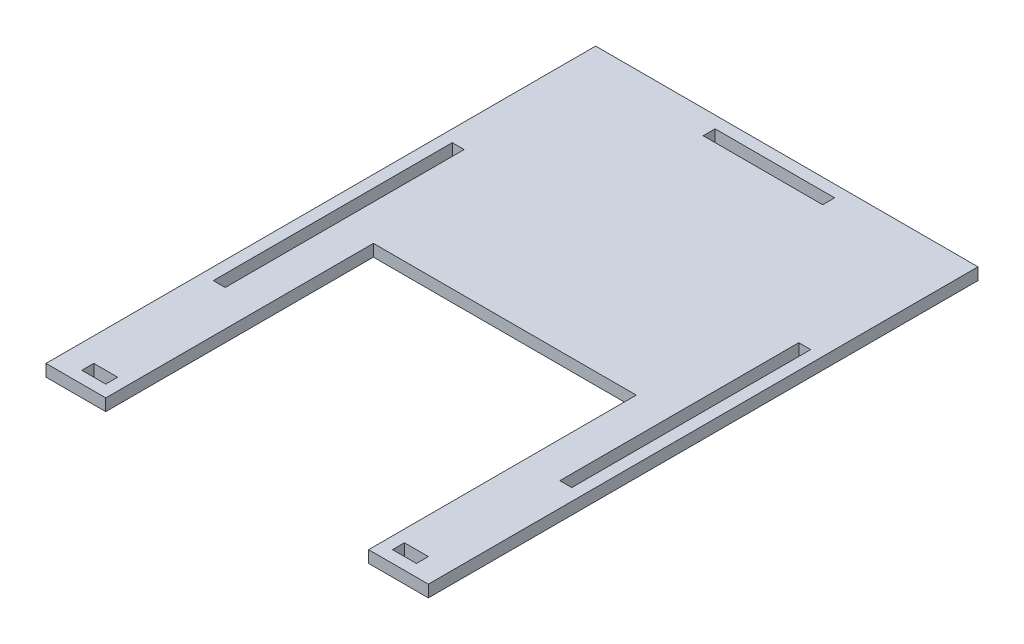
SolidWorks part; units mm, degrees
ref_plane "Front Plane" through (0, 0, 0) normal (0, 0, 1) x (1, 0, 0)
ref_plane "Top Plane" through (0, 0, 0) normal (0, 1, 0) x (1, 0, 0)
ref_plane "Right Plane" through (0, 0, 0) normal (1, 0, 0) x (0, 0, -1)
sketch "Sketch1" plane through (0, 0, 0) normal (0, 1, 0) x (1, 0, 0)
  line L0 (0, 69.85) -> (0, 66.675) construction
  line L1 (-44.45, 66.675) -> (44.45, 66.675) construction
  line L2 (-44.45, 66.675) -> (-44.45, -66.675) construction
  line L3 (38.1, -66.675) -> (34.925, -66.675) construction
  line L4 (44.45, 66.675) -> (44.45, -66.675) construction
  line L5 (-50.8, 73.025) -> (50.8, 73.025)
  line L6 (-50.8, 73.025) -> (-50.8, -73.025)
  line L7 (-50.8, -73.025) -> (-34.925, -73.025)
  line L8 (50.8, 73.025) -> (50.8, -73.025)
  line L9 (-15.875, 69.85) -> (15.875, 69.85)
  line L10 (-15.875, 69.85) -> (-15.875, 66.675)
  line L11 (-15.875, 66.675) -> (15.875, 66.675)
  line L12 (15.875, 69.85) -> (15.875, 66.675)
  line L13 (-44.45, 31.75) -> (-47.625, 31.75)
  line L14 (-44.45, 31.75) -> (-44.45, -31.75)
  line L15 (-44.45, -31.75) -> (-47.625, -31.75)
  line L16 (-47.625, 31.75) -> (-47.625, -31.75)
  line L17 (44.45, 31.75) -> (47.625, 31.75)
  line L18 (44.45, 31.75) -> (44.45, -31.75)
  line L19 (44.45, -31.75) -> (47.625, -31.75)
  line L20 (47.625, 31.75) -> (47.625, -31.75)
  line L21 (-44.45, -66.675) -> (-38.1, -66.675)
  line L22 (-44.45, -66.675) -> (-44.45, -69.85)
  line L23 (-44.45, -69.85) -> (-38.1, -69.85)
  line L24 (-38.1, -66.675) -> (-38.1, -69.85)
  line L25 (38.1, -66.675) -> (44.45, -66.675)
  line L26 (38.1, -66.675) -> (38.1, -69.85)
  line L27 (38.1, -69.85) -> (44.45, -69.85)
  line L28 (44.45, -66.675) -> (44.45, -69.85)
  line L29 (0, 73.025) -> (0, -73.025) construction
  line L30 (-34.925, -73.025) -> (-34.925, -1.905)
  line L31 (-34.925, -1.905) -> (34.925, -1.905)
  line L32 (34.925, -1.905) -> (34.925, -73.025)
  line L33 (-47.625, 0) -> (47.625, 0) construction
  line L35 (-38.1, -66.675) -> (-34.925, -66.675) construction
  line L37 (34.925, -73.025) -> (50.8, -73.025)
  line L38 (-34.925, -73.025) -> (34.925, -73.025) construction
  line L39 (34.925, -73.025) -> (35.2486, -72.0129) construction
  point P37 (0, -1.905)
  dimension "D1" = 88.9
  dimension "D2" = 133.35
  dimension "D3" = 3.175
  dimension "D4" = 3.175
  dimension "D5" = 3.175
  dimension "D6" = 31.75
  dimension "D7" = 63.5
  dimension "D8" = 63.5
  dimension "D9" = 3.175
  dimension "D10" = 3.175
  dimension "D11" = 3.175
  dimension "D12" = 3.175
  dimension "D13" = 3.175
  dimension "D14" = 6.35
  dimension "D15" = 6.35
  dimension "D16" = 69.85
  dimension "D17" = 68.58
extrude "Boss-Extrude1" add sketch "Sketch1" along normal blind 3.175
